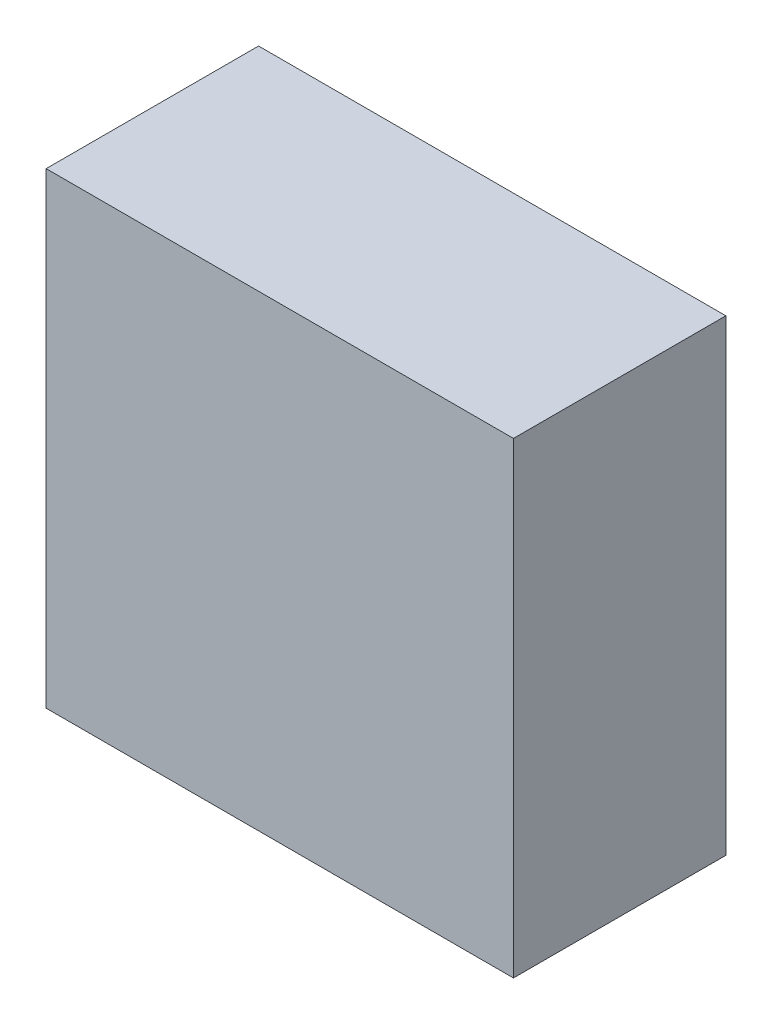
SolidWorks part; units mm, degrees
ref_plane "前视基准面" through (0, 0, 0) normal (0, 0, 1) x (1, 0, 0)
ref_plane "上视基准面" through (0, 0, 0) normal (0, 1, 0) x (1, 0, 0)
ref_plane "右视基准面" through (0, 0, 0) normal (1, 0, 0) x (0, 0, -1)
sketch "edrawing" plane through (0, 0, 0) normal (0, 0, 1) x (1, 0, 0)
  line L1 (0, 0) -> (11, 0)
  line L2 (0, 0) -> (0, 11)
  line L3 (0, 11) -> (11, 11)
  line L4 (11, 0) -> (11, 11)
  dimension "DS_D1" = 11
  dimension "DS_D2" = 11
extrude "extrude1" add sketch "edrawing" along normal blind 5
